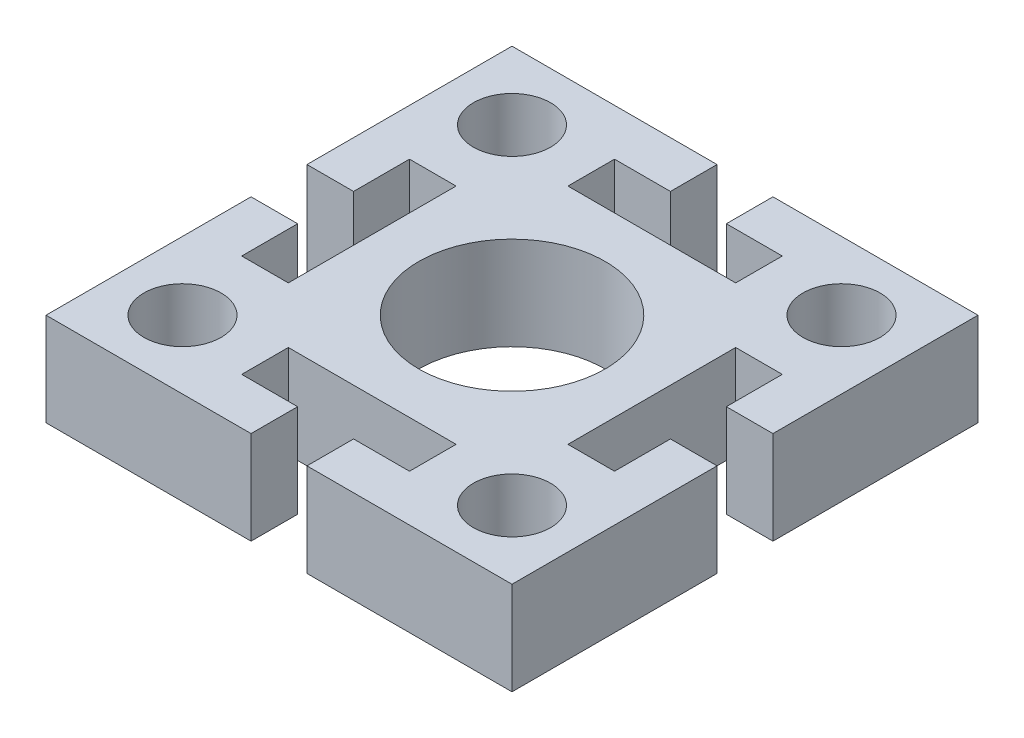
SolidWorks part; units mm, degrees
ref_plane "Front Plane" through (0, 0, 0) normal (0, 0, 1) x (1, 0, 0)
ref_plane "Top Plane" through (0, 0, 0) normal (0, 1, 0) x (1, 0, 0)
ref_plane "Right Plane" through (0, 0, 0) normal (1, 0, 0) x (0, 0, -1)
sketch "Sketch1" plane through (0, 0, 0) normal (0, 1, 0) x (1, 0, 0)
  line L1 (-25, -3) -> (-25, -25)
  line L6 (9, 20) -> (9, 15)
  line L7 (9, 20) -> (3, 20)
  line L8 (9, 15) -> (-9, 15)
  line L9 (3, 20) -> (3, 25)
  line L10 (-3, 25) -> (-25, 25)
  line L11 (-25, 25) -> (-25, 3)
  line L12 (-25, -25) -> (-3, -25)
  line L13 (25, -25) -> (25, -3)
  line L14 (3, 25) -> (25, 25)
  line L15 (-3, 20) -> (-3, 25)
  line L16 (-9, 20) -> (-9, 15)
  line L17 (3, -25) -> (25, -25)
  line L18 (25, 3) -> (25, 25)
  line L19 (-3, 20) -> (-9, 20)
  line L21 (-20, 9) -> (-15, 9)
  line L22 (-20, 9) -> (-20, 3)
  line L24 (-15, 9) -> (-15, -9)
  line L27 (-20, 3) -> (-25, 3)
  line L28 (20, -9) -> (15, -9)
  line L29 (20, -9) -> (20, -3)
  line L30 (15, -9) -> (15, 9)
  line L31 (20, -3) -> (25, -3)
  line L32 (20, 3) -> (25, 3)
  line L33 (-20, -3) -> (-25, -3)
  line L34 (20, 9) -> (15, 9)
  line L35 (20, 3) -> (20, 9)
  line L40 (-20, -9) -> (-15, -9)
  line L41 (-20, -3) -> (-20, -9)
  line L42 (-9, -20) -> (-9, -15)
  line L43 (-9, -20) -> (-3, -20)
  line L44 (-9, -15) -> (9, -15)
  line L45 (-3, -20) -> (-3, -25)
  line L46 (3, -20) -> (3, -25)
  line L47 (9, -20) -> (9, -15)
  line L48 (3, -20) -> (9, -20)
  circle A0 centre (0, 0) radius 10
  circle A1 centre (-17.6777, 17.6777) radius 4.1387
  circle A2 centre (17.6777, 17.6777) radius 4.1387
  circle A3 centre (17.6777, -17.6777) radius 4.1387
  circle A4 centre (-17.6777, -17.6777) radius 4.1387
  point P44 (0, 0)
  point P46 (0, 0)
  dimension "D1" = 4
extrude "Boss-Extrude1" add sketch "Sketch1" along normal blind 10
